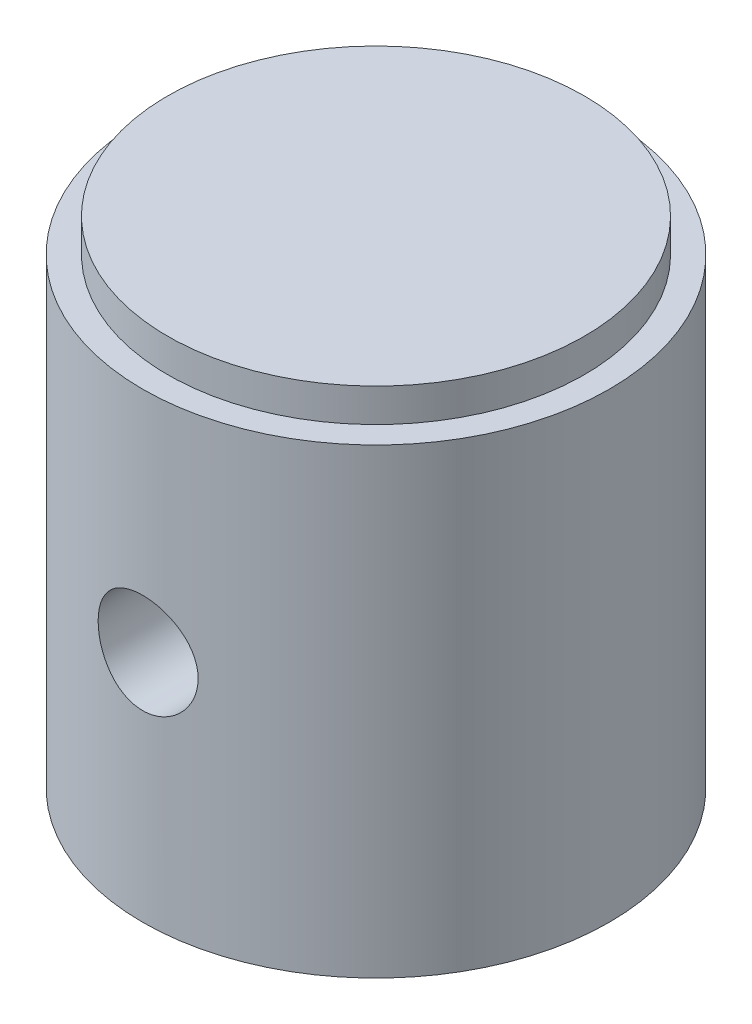
SolidWorks part; units mm, degrees
ref_plane "Front Plane" through (0, 0, 0) normal (0, 0, 1) x (1, 0, 0)
ref_plane "Top Plane" through (0, 0, 0) normal (0, 1, 0) x (1, 0, 0)
ref_plane "Right Plane" through (0, 0, 0) normal (1, 0, 0) x (0, 0, -1)
sketch "Sketch1" plane through (0, 0, 0) normal (1, 0, 0) x (0, 0, -1)
  line L0 (0, 0) -> (0, 14.8541) construction
  line L1 (0, 14.8541) -> (-6.25, 14.8541)
  line L2 (-6.25, 14.8541) -> (-6.25, 13.8541)
  line L3 (-6.25, 13.8541) -> (-7, 13.8541)
  line L4 (-7, 13.8541) -> (-7, 0)
  line L5 (-7, 0) -> (-6.2, 0)
  line L6 (-6.2, 0) -> (-4.75, 3.9838)
  line L7 (-4.75, 3.9838) -> (-4.75, 11)
  line L8 (-4.75, 11) -> (0, 13.8541)
  line L9 (0, 13.8541) -> (0, 14.8541)
  point P3 (-5.7361, 0)
  point P12 (0, 13.8541)
  point P13 (0, 13.8541)
  dimension "D1" = 11
  dimension "D2" = 6.25
  dimension "D3" = 7
  dimension "D4" = 1
  dimension "D5" = 70
  dimension "D6" = 59
  dimension "D7" = 4.75
  dimension "D8" = 6.2
  dimension "D9" = 1
revolve "Revolve1" add sketch "Sketch1" angle 360 about L0
sketch "Sketch2" plane through (0, 0, 0) normal (0, 0, 1) x (1, 0, 0)
  line L0 (0, 0) -> (0, 7) construction
  circle A0 centre (0, 7) radius 1.5
  dimension "D1" = 3
extrude "Cut-Extrude1" cut sketch "Sketch2" against normal through all both and the other way through all
